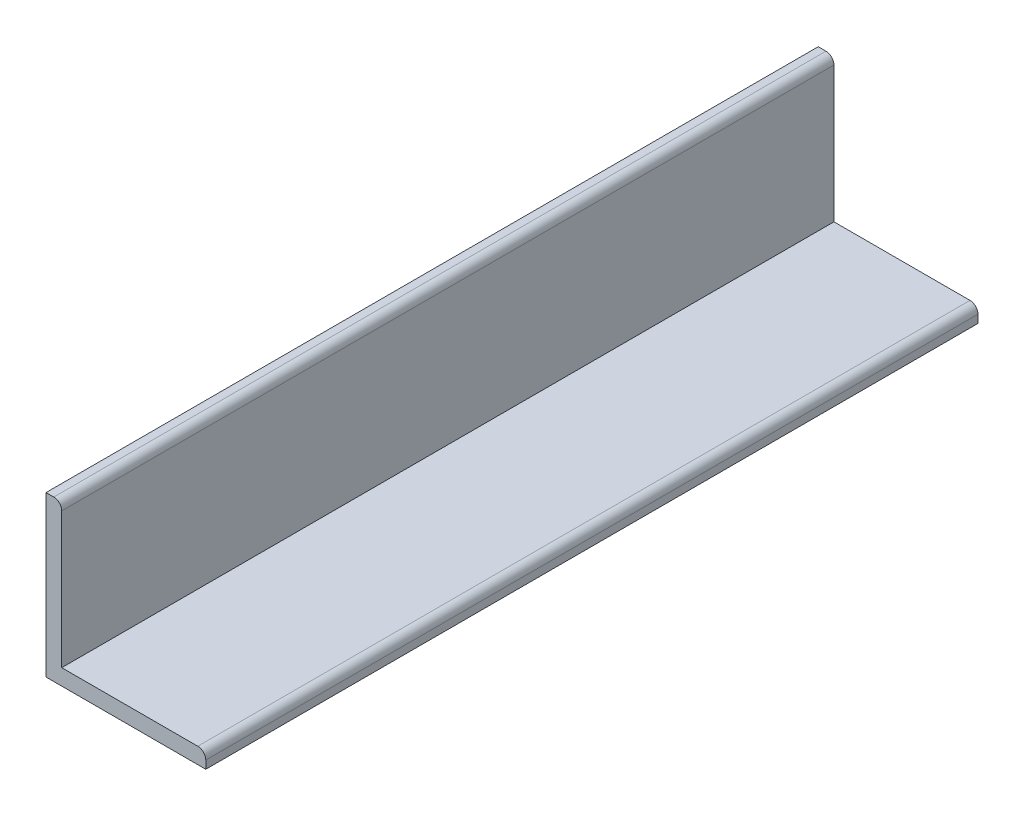
SolidWorks part; units mm, degrees
material "ASTM A36 Steel"
ref_plane "Front Plane" through (0, 0, 0) normal (0, 0, 1) x (1, 0, 0)
ref_plane "Top Plane" through (0, 0, 0) normal (0, 1, 0) x (1, 0, 0)
ref_plane "Right Plane" through (0, 0, 0) normal (1, 0, 0) x (0, 0, -1)
sketch "Sketch1" plane through (0, 0, 0) normal (0, 0, 1) x (1, 0, 0)
  line L0 (-23.8632, 26.7732) -> (-23.8632, -24.2268)
  line L1 (-29.7732, -30.2268) -> (30.2268, -30.2268)
  line L2 (-29.7732, -30.2268) -> (-29.7732, 29.7732)
  line L3 (-29.7732, 29.7732) -> (-26.8632, 29.7732)
  line L4 (30.2268, -30.2268) -> (30.2268, -27.2268)
  line L5 (-29.7732, -30.2268) -> (19.8474, 20.1498) construction
  line L6 (-29.7732, 29.7732) -> (30.2268, -30.2268) construction
  line L7 (-23.8632, -24.2268) -> (27.2268, -24.2268)
  arc A0 (27.2268, -24.2268) -> (30.2268, -27.2268) centre (27.2268, -27.2268) cw
  arc A1 (-23.8632, 26.7732) -> (-26.8632, 29.7732) centre (-26.8632, 26.7732) ccw
  point P0 (0, 0)
  dimension "D4" = 3
  dimension "D1" = 60
  dimension "D2" = 60
  dimension "D3" = 6
extrude "Boss-Extrude1" add sketch "Sketch1" along normal mid plane 290
